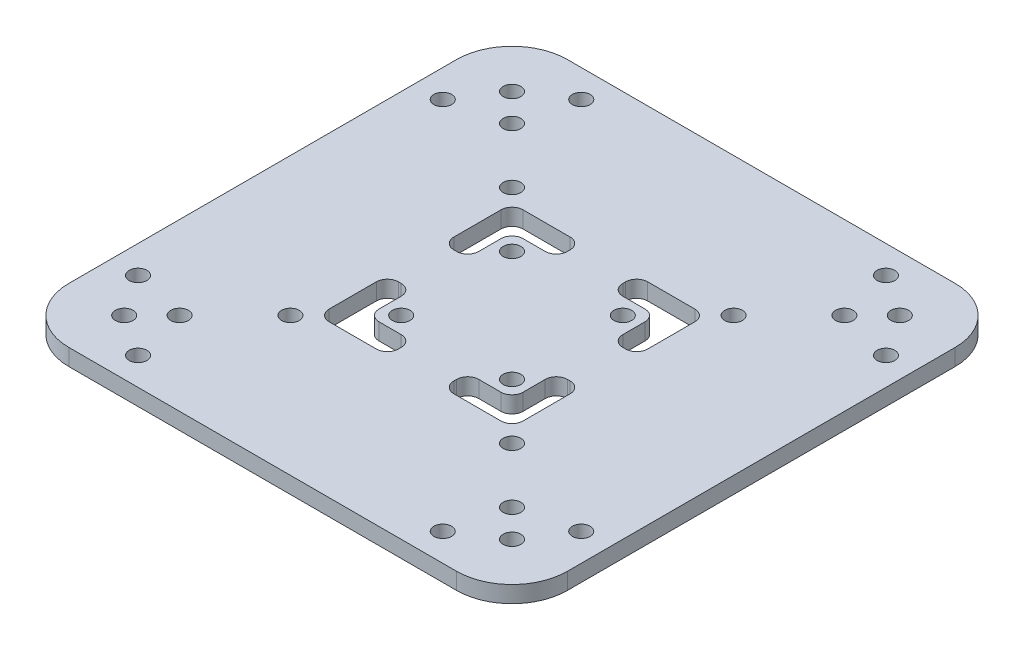
SolidWorks part; units mm, degrees
material "Thornel Mat VMA"
ref_plane "前视基准面" through (0, 0, 0) normal (0, 0, 1) x (1, 0, 0)
ref_plane "上视基准面" through (0, 0, 0) normal (0, 1, 0) x (1, 0, 0)
ref_plane "右视基准面" through (0, 0, 0) normal (1, 0, 0) x (0, 0, -1)
other "Configuration Table"
sketch "草图1" plane through (0, 0, 0) normal (0, 1, 0) x (1, 0, 0)
  line L1 (35, -35) -> (-35, -35) construction
  line L2 (35, -35) -> (35, 35) construction
  line L3 (35, 35) -> (-35, 35) construction
  line L4 (-35, -35) -> (-35, 35) construction
  line L5 (35, -35) -> (-35, 35) construction
  line L6 (35, 35) -> (-35, -35) construction
  line L7 (45, -45) -> (-45, -45)
  line L8 (45, -45) -> (45, 45)
  line L9 (45, 45) -> (-45, 45)
  line L10 (-45, -45) -> (-45, 45)
  line L11 (45, -45) -> (-45, 45) construction
  line L12 (45, 45) -> (-45, -45) construction
  line L13 (13, -13) -> (-13, -13)
  line L14 (13, -13) -> (13, 13)
  line L15 (13, 13) -> (-13, 13)
  line L16 (-13, -13) -> (-13, 13)
  line L17 (13, -13) -> (-13, 13) construction
  line L18 (13, 13) -> (-13, -13) construction
  line L19 (17.5, -17.5) -> (-17.5, -17.5)
  line L20 (17.5, -17.5) -> (17.5, 17.5)
  line L21 (17.5, 17.5) -> (-17.5, 17.5)
  line L22 (-17.5, -17.5) -> (-17.5, 17.5)
  line L23 (17.5, -17.5) -> (-17.5, 17.5) construction
  line L24 (17.5, 17.5) -> (-17.5, -17.5) construction
  line L25 (5, -17.5) -> (-5, -17.5)
  line L26 (5, -17.5) -> (5, 17.5)
  line L27 (5, 17.5) -> (-5, 17.5)
  line L28 (-5, -17.5) -> (-5, 17.5)
  line L29 (5, -17.5) -> (-5, 17.5) construction
  line L30 (5, 17.5) -> (-5, -17.5) construction
  line L31 (17.5, -5) -> (-17.5, -5)
  line L32 (17.5, -5) -> (17.5, 5)
  line L33 (17.5, 5) -> (-17.5, 5)
  line L34 (-17.5, -5) -> (-17.5, 5)
  line L35 (17.5, -5) -> (-17.5, 5) construction
  line L36 (17.5, 5) -> (-17.5, -5) construction
  circle A0 centre (-35, 35) radius 1.6
  circle A1 centre (35, 35) radius 1.6
  circle A2 centre (35, -35) radius 1.6
  circle A3 centre (-35, -35) radius 1.6
  circle A4 centre (-10, 10) radius 1.6
  circle A5 centre (10, 10) radius 1.6
  circle A6 centre (10, -10) radius 1.6
  circle A7 centre (-10, -10) radius 1.6
  point P0 (0, 0)
  point P10 (0, 0)
  point P15 (0, 0)
  point P20 (0, 0)
  point P25 (0, 0)
  point P30 (0, 0)
  point P46 (0, 0)
  dimension "D3" = 3.2
  dimension "D14" = 3.2
  dimension "D1" = 70
  dimension "D2" = 70
  dimension "D4" = 10
  dimension "D5" = 10
  dimension "D6" = 26
  dimension "D7" = 26
  dimension "D8" = 35
  dimension "D10" = 10
  dimension "D11" = 10
  dimension "D13" = 20
  dimension "D12" = 4
extrude "凸台-拉伸1" add sketch "草图1" along normal blind 3 contours L10 L7 L8 L9 A3 A2 A1 A0 L19 L22 L21 L20 | L28 L15 L26 L21 | L13 L28 L15 L16 | L28 L13 L26 L15 | L26 L13 L14 L15 | L28 L19 L26 L13 | L33 L26 L15 L28 | L26 L31 L28 L13 | L28 L31 L16 L13 | L33 L28 L15 L16 | L33 L14 L15 L26 | L14 L31 L26 L13 | L20 L33 L14 L31 | L16 L33 L22 L31
sketch "草图3" plane through (0, 3, 0) normal (0, 1, 0) x (1, 0, 0)
  line L1 (20, -20) -> (-20, -20) construction
  line L2 (20, -20) -> (20, 20) construction
  line L3 (20, 20) -> (-20, 20) construction
  line L4 (-20, -20) -> (-20, 20) construction
  line L5 (20, -20) -> (-20, 20) construction
  line L6 (20, 20) -> (-20, -20) construction
  circle A0 centre (-20, 20) radius 1.6
  circle A1 centre (20, 20) radius 1.6
  circle A2 centre (20, -20) radius 1.6
  circle A3 centre (-20, -20) radius 1.6
  point P0 (0, 0)
  dimension "D3" = 3.2
  dimension "D1" = 40
  dimension "D2" = 40
extrude "切除-拉伸2" cut sketch "草图3" against normal through all
fillet "圆角1" radius 2 24 edges at (17.5, 1.5, 17.5) (17.5, 1.5, 5) (13, 1.5, 5) (13, 1.5, 13) (5, 1.5, 13) (5, 1.5, 17.5) (-5, 1.5, 13) (-13, 1.5, 13) (-13, 1.5, 5) (-17.5, 1.5, 5) (-17.5, 1.5, 17.5) (-5, 1.5, 17.5) (-5, 1.5, -17.5) (-17.5, 1.5, -17.5) (-17.5, 1.5, -5) (-13, 1.5, -5) (-13, 1.5, -13) (-5, 1.5, -13) (17.5, 1.5, -5) (17.5, 1.5, -17.5) (5, 1.5, -17.5) (5, 1.5, -13) (13, 1.5, -13) (13, 1.5, -5)
sketch "草图5" plane through (0, 3, 0) normal (0, 1, 0) x (1, 0, 0)
  line L0 (45, 45) -> (-45, 45) construction
  line L1 (20, 25) -> (-20, 25)
  line L2 (20, 25) -> (20, 40)
  line L3 (20, 40) -> (-20, 40)
  line L4 (-20, 25) -> (-20, 40)
  line L5 (20, 25) -> (-20, 40) construction
  line L6 (20, 40) -> (-20, 25) construction
  line L7 (25, -20) -> (25, 20)
  line L8 (25, -20) -> (40, -20)
  line L9 (40, -20) -> (40, 20)
  line L10 (25, 20) -> (40, 20)
  line L11 (25, -20) -> (40, 20) construction
  line L12 (40, -20) -> (25, 20) construction
  line L13 (-20, -25) -> (20, -25)
  line L14 (-20, -25) -> (-20, -40)
  line L15 (-20, -40) -> (20, -40)
  line L16 (20, -25) -> (20, -40)
  line L17 (-20, -25) -> (20, -40) construction
  line L18 (-20, -40) -> (20, -25) construction
  line L19 (-25, 20) -> (-25, -20)
  line L20 (-25, 20) -> (-40, 20)
  line L21 (-40, 20) -> (-40, -20)
  line L22 (-25, -20) -> (-40, -20)
  line L23 (-25, 20) -> (-40, -20) construction
  line L24 (-40, 20) -> (-25, -20) construction
  point P0 (0, 32.5)
  point P11 (32.5, 0)
  point P16 (0, -32.5)
  point P21 (-32.5, 0)
  point P26 (0, 0)
  dimension "D1" = 5
  dimension "D2" = 15
  dimension "D3" = 40
  dimension "D4" = 4
extrude "切除-拉伸3" [suppressed] cut sketch "草图5" against normal through all
fillet "圆角2" [suppressed] radius 2
fillet "圆角3" radius 10 4 edges at (-45, 1.5, -45) (45, 1.5, -45) (45, 1.5, 45) (-45, 1.5, 45)
sketch "草图6" plane through (0, 3, 0) normal (0, 1, 0) x (1, 0, 0)
  line L1 (27.5, -40) -> (-27.5, -40) construction
  line L2 (27.5, -40) -> (27.5, 40) construction
  line L3 (27.5, 40) -> (-27.5, 40) construction
  line L4 (-27.5, -40) -> (-27.5, 40) construction
  line L5 (27.5, -40) -> (-27.5, 40) construction
  line L6 (27.5, 40) -> (-27.5, -40) construction
  circle A0 centre (-27.5, 40) radius 1.6
  circle A1 centre (27.5, 40) radius 1.6
  circle A2 centre (40, 27.5) radius 1.6
  circle A3 centre (27.5, -40) radius 1.6
  circle A4 centre (-40, -27.5) radius 1.6
  circle A5 centre (40, -27.5) radius 1.6
  circle A6 centre (-27.5, -40) radius 1.6
  circle A7 centre (-40, 27.5) radius 1.6
  point P0 (0, 0)
  point P17 (0, 0)
  point P23 (0, 0)
  dimension "D3" = 3.2
  dimension "D1" = 80
  dimension "D2" = 55
  dimension "D4" = 4
  dimension "D5" = 4
extrude "切除-拉伸4" cut sketch "草图6" against normal through all
sketch "草图8" [suppressed] plane through (0, 3, 0) normal (0, 1, 0) x (1, 0, 0)
  line L0 (-40, 18) -> (-40, -18) construction
  line L1 (-25, -5) -> (-40, -5)
  line L2 (-25, -5) -> (-25, 5)
  line L3 (-25, 5) -> (-40, 5)
  line L4 (-40, -5) -> (-40, 5)
  line L5 (-25, -5) -> (-40, 5) construction
  line L6 (-25, 5) -> (-40, -5) construction
  line L7 (-25, -18) -> (-25, 18) construction
  line L8 (-5, 25) -> (-5, 40)
  line L9 (-5, 25) -> (5, 25)
  line L10 (5, 25) -> (5, 40)
  line L11 (-5, 40) -> (5, 40)
  line L12 (-5, 25) -> (5, 40) construction
  line L13 (5, 25) -> (-5, 40) construction
  line L14 (25, 5) -> (40, 5)
  line L15 (25, 5) -> (25, -5)
  line L16 (25, -5) -> (40, -5)
  line L17 (40, 5) -> (40, -5)
  line L18 (25, 5) -> (40, -5) construction
  line L19 (25, -5) -> (40, 5) construction
  line L20 (5, -25) -> (5, -40)
  line L21 (5, -25) -> (-5, -25)
  line L22 (-5, -25) -> (-5, -40)
  line L23 (5, -40) -> (-5, -40)
  line L24 (5, -25) -> (-5, -40) construction
  line L25 (-5, -25) -> (5, -40) construction
  line L26 (18, -25) -> (-18, -25) construction
  line L27 (25, 18) -> (25, -18) construction
  point P0 (-32.5, 0)
  point P10 (0, 32.5)
  point P18 (32.5, 0)
  point P23 (0, -32.5)
  point P28 (0, 0)
  dimension "D1" = 10
  dimension "D2" = 4
extrude "凸台-拉伸2" [suppressed] add sketch "草图8" against normal up to surface (3 mm away)
fillet "圆角4" [suppressed] radius 2
sketch "草图9" [suppressed] plane through (0, 3, 0) normal (0, 1, 0) x (1, 0, 0)
  line L0 (-20, 38) -> (-20, 27) construction
  line L1 (20, 30) -> (-20, 30)
  line L2 (20, 30) -> (20, 35)
  line L3 (20, 35) -> (-20, 35)
  line L4 (-20, 30) -> (-20, 35)
  line L5 (20, 30) -> (-20, 35) construction
  line L6 (20, 35) -> (-20, 30) construction
  line L7 (-5, 38) -> (-5, 27) construction
  line L8 (30, -20) -> (30, 20)
  line L9 (30, -20) -> (35, -20)
  line L10 (35, -20) -> (35, 20)
  line L11 (30, 20) -> (35, 20)
  line L12 (30, -20) -> (35, 20) construction
  line L13 (35, -20) -> (30, 20) construction
  line L14 (-20, -30) -> (20, -30)
  line L15 (-20, -30) -> (-20, -35)
  line L16 (-20, -35) -> (20, -35)
  line L17 (20, -30) -> (20, -35)
  line L18 (-20, -30) -> (20, -35) construction
  line L19 (-20, -35) -> (20, -30) construction
  line L20 (-30, 20) -> (-30, -20)
  line L21 (-30, 20) -> (-35, 20)
  line L22 (-35, 20) -> (-35, -20)
  line L23 (-30, -20) -> (-35, -20)
  line L24 (-30, 20) -> (-35, -20) construction
  line L25 (-35, 20) -> (-30, -20) construction
  line L26 (-38, -20) -> (-27, -20) construction
  point P0 (0, 32.5)
  point P10 (-5, 32.5)
  point P11 (32.5, 0)
  point P19 (0, -32.5)
  point P24 (-32.5, 0)
  point P29 (0, 0)
  dimension "D1" = 5
  dimension "D2" = 4
extrude "凸台-拉伸3" [suppressed] add sketch "草图9" against normal up to surface (3 mm away)
fillet "圆角5" [suppressed] radius 2
sketch "草图12" plane through (0, 3, 0) normal (0, 1, 0) x (1, 0, 0)
  line L1 (30, -30) -> (-30, -30) construction
  line L2 (30, -30) -> (30, 30) construction
  line L3 (30, 30) -> (-30, 30) construction
  line L4 (-30, -30) -> (-30, 30) construction
  line L5 (30, -30) -> (-30, 30) construction
  line L6 (30, 30) -> (-30, -30) construction
  circle A0 centre (-30, 30) radius 1.6
  circle A1 centre (30, 30) radius 1.6
  circle A2 centre (30, -30) radius 1.6
  circle A3 centre (-30, -30) radius 1.6
  point P0 (0, 0)
  point P16 (0, 0)
  dimension "D2" = 3.2
  dimension "D1" = 60
  dimension "D3" = 4
extrude "切除-拉伸5" cut sketch "草图12" against normal through all
